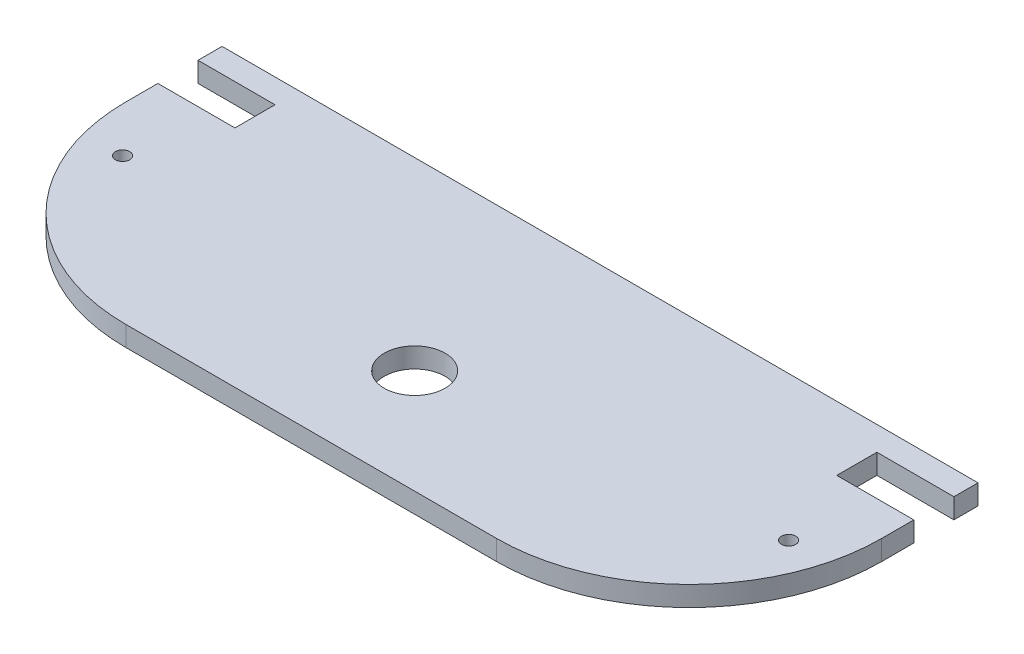
SolidWorks part; units mm, degrees
material "Acrylic (Medium-high impact)"
ref_plane "Front Plane" through (0, 0, 0) normal (0, 0, 1) x (1, 0, 0)
ref_plane "Top Plane" through (0, 0, 0) normal (0, 1, 0) x (1, 0, 0)
ref_plane "Right Plane" through (0, 0, 0) normal (1, 0, 0) x (0, 0, -1)
sketch "Sketch1" plane through (0, 0, 0) normal (0, 1, 0) x (1, 0, 0)
  line L1 (0, 0) -> (119.634, 0)
  line L2 (0, 0) -> (0, 41.91)
  line L3 (0, 41.91) -> (119.634, 41.91)
  line L4 (119.634, 0) -> (119.634, 41.91)
  circle A0 centre (59.69, 16.51) radius 4.8133
  dimension "D3" = 9.6266
  dimension "D1" = 119.634
  dimension "D2" = 41.91
  dimension "D4" = 59.69
  dimension "D5" = 25.4
extrude "Boss-Extrude1" add sketch "Sketch1" along normal blind 3.175
sketch "Sketch3" plane through (0, 3.175, 0) normal (0, 1, 0) x (1, 0, 0)
  line L1 (0, 41.91) -> (12.192, 41.91)
  line L2 (0, 41.91) -> (0, 35.56)
  line L3 (0, 35.56) -> (12.192, 35.56)
  line L4 (12.192, 41.91) -> (12.192, 35.56)
  line L5 (119.634, 41.91) -> (107.442, 41.91)
  line L6 (119.634, 41.91) -> (119.634, 35.56)
  line L7 (119.634, 35.56) -> (107.442, 35.56)
  line L8 (107.442, 41.91) -> (107.442, 35.56)
  point P10 (12.192, 38.735)
  point P11 (6.096, 35.56)
  dimension "D1" = 12.192
  dimension "D2" = 6.35
  dimension "D3" = 12.192
  dimension "D4" = 6.35
extrude "Cut-Extrude2" cut sketch "Sketch3" against normal blind 22.352
fillet "Fillet1" radius 30.48 2 edges at (0, 1.5875, 0) (119.634, 1.5875, 0)
sketch "Sketch4" plane through (0, 0, -41.91) normal (0, 0, -1) x (-1, 0, 0)
  line L0 (0, 0) -> (0, 3.175) construction
  line L1 (-119.634, 0) -> (0, 0)
  line L2 (-119.634, 0) -> (-119.634, 3.175)
  line L3 (-119.634, 3.175) -> (0, 3.175)
  line L4 (0, 0) -> (0, 3.175)
extrude "Boss-Extrude2" add sketch "Sketch4" along normal blind 3.81
sketch "Sketch5" plane through (0, 0, 0) normal (0, -1, 0) x (1, 0, 0)
  circle A0 centre (7.112, -22.86) radius 1.1303
  dimension "D1" = 2.2606
extrude "Cut-Extrude3" cut sketch "Sketch5" against normal blind 6.35
sketch "Sketch6" plane through (0, 0, 0) normal (0, -1, 0) x (1, 0, 0)
  circle A0 centre (112.522, -22.86) radius 1.1303
  dimension "D1" = 2.2606
extrude "Cut-Extrude4" cut sketch "Sketch6" against normal blind 6.35
